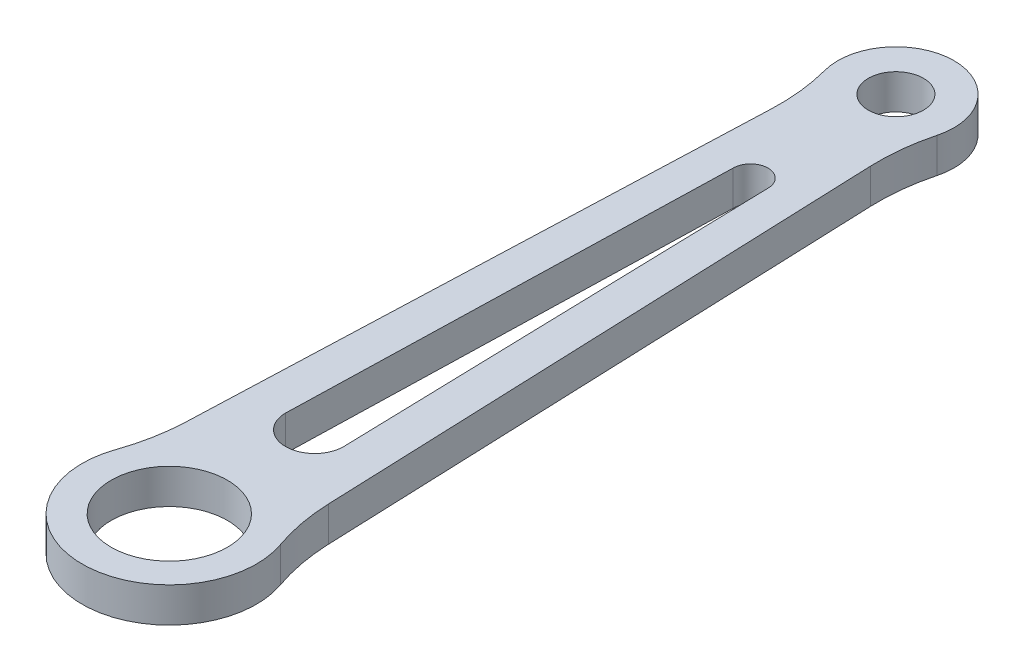
SolidWorks part; units mm, degrees
material "Thornel Mat VMA"
ref_plane "前视基准面" through (0, 0, 0) normal (0, 0, 1) x (1, 0, 0)
ref_plane "上视基准面" through (0, 0, 0) normal (0, 1, 0) x (1, 0, 0)
ref_plane "右视基准面" through (0, 0, 0) normal (1, 0, 0) x (0, 0, -1)
sketch "草图1" plane through (0, 0, 0) normal (0, 1, 0) x (1, 0, 0)
  line L0 (0, 0) -> (0, 250) construction
  line L1 (-17.9929, -0.504) -> (-24.9902, 249.3)
  line L2 (17.9929, -0.504) -> (24.9902, 249.3)
  line L3 (-11.9953, -0.336) -> (-18.9926, 249.468) construction
  line L4 (11.9953, -0.336) -> (18.9926, 249.468) construction
  line L5 (-16.4444, 158.5) -> (15.7446, 133.5146) construction
  line L6 (15.7446, 133.5146) -> (18.4752, 231) construction
  line L7 (18.4752, 231) -> (-18.0888, 217.2024) construction
  line L8 (-18.0888, 217.2024) -> (-16.4444, 158.5) construction
  line L9 (15.7446, 133.5146) -> (-18.0888, 217.2024) construction
  line L10 (18.5259, 134.639) -> (-15.3075, 218.3268) construction
  line L11 (12.9633, 132.3901) -> (-20.8701, 216.0779) construction
  line L12 (-16.4444, 158.5) -> (-17.7049, 203.5)
  line L13 (-17.7049, 203.5) -> (11.0289, 137.1749)
  line L14 (11.0289, 137.1749) -> (-16.4444, 158.5)
  line L15 (15.9543, 141) -> (18.4752, 231)
  line L16 (-15.3075, 218.3268) -> (-13.7162, 214.3907) construction
  line L17 (18.4752, 231) -> (-12, 219.5)
  line L18 (-12, 219.5) -> (15.9543, 141)
  circle A0 centre (0, 250) radius 25 construction
  circle A1 centre (0, 0) radius 18 construction
  circle A2 centre (0, 0) radius 5.05
  circle A3 centre (0, 250) radius 9.5
  arc A4 (-17.9929, -0.504) -> (17.9929, -0.504) centre (0, 0) ccw
  arc A5 (-24.9902, 249.3) -> (24.9902, 249.3) centre (0, 250) cw
  arc A6 (-18.9926, 249.468) -> (18.9926, 249.468) centre (0, 250) cw construction
  arc A7 (-11.9953, -0.336) -> (11.9953, -0.336) centre (0, 0) ccw construction
  dimension "D2" = 50
  dimension "D3" = 36
  dimension "D4" = 10.1
  dimension "D5" = 19
  dimension "D1" = 250
  dimension "D9" = 19
  dimension "D10" = 30.5
  dimension "D11" = 16
  dimension "D12" = 45
  dimension "D13" = 90
  dimension "D14" = 12
  dimension "D6" = 6
  dimension "D7" = 3
  dimension "D8" = 3
extrude "凸台-拉伸1" add sketch "草图1" along normal blind 12
fillet "圆角1" radius 3 6 edges at (18.4752, 6, -231) (-12, 6, -219.5) (-17.7049, 6, -203.5) (-16.4444, 6, -158.5) (15.9543, 6, -141) (11.0289, 6, -137.1749)
sketch "草图2" plane through (0, 12, 0) normal (0, 1, 0) x (1, 0, 0)
  line L0 (0, 250) -> (-15, 250) construction
  circle A0 centre (-15, 250) radius 2
  dimension "D2" = 4
  dimension "D1" = 15
extrude "切除-拉伸1" [suppressed] cut sketch "草图2" against normal through all
pattern_circular "阵列(圆周)1" [suppressed] count 3 over 360
sketch "草图3" plane through (0, 12, 0) normal (0, 1, 0) x (1, 0, 0)
  line L0 (0, 250) -> (14.25, 250) construction
  circle A0 centre (14.25, 250) radius 2
  dimension "D2" = 4
  dimension "D1" = 14.25
extrude "切除-拉伸2" [suppressed] cut sketch "草图3" against normal through all
pattern_circular "阵列(圆周)2" [suppressed] count 3 over 360
sketch "草图4" plane through (0, 12, 0) normal (0, 1, 0) x (1, 0, 0)
  line L2 (8.9965, -0.252) -> (15.9937, 249.552)
  line L3 (8.9965, -0.252) -> (15.9937, 249.552) construction
  line L4 (-13.0503, 144.4724) -> (12.4949, 124.6439)
  line L5 (-15.9937, 249.552) -> (-8.9965, -0.252)
  line L6 (-15.9937, 249.552) -> (-8.9965, -0.252) construction
  line L7 (-15.3248, 157.6309) -> (1.7846, 144.3504) construction
  line L8 (12.4949, 124.6439) -> (9.7421, 26.3657)
  line L9 (9.7421, 26.3657) -> (-10.1751, 41.8256)
  line L10 (-10.1751, 41.8256) -> (-13.0503, 144.4724)
  dimension "D3" = 9
  dimension "D1" = 9
  dimension "D2" = 9
extrude "切除-拉伸3" [suppressed] cut sketch "草图4" against normal through all
fillet "圆角2" [suppressed] radius 3
sketch "草图5" plane through (0, 12, 0) normal (0, 1, 0) x (1, 0, 0)
  circle A0 centre (0, 0) radius 27.5
  circle A1 centre (0, 0) radius 5.05
  dimension "D1" = 55
extrude "凸台-拉伸2" [suppressed] add sketch "草图5" against normal up to surface (10 mm away)
fillet "圆角3" [suppressed] radius 6
sketch "草图6" [suppressed] plane through (0, 15, 0) normal (0, 1, 0) x (1, 0, 0)
  line L0 (12.4949, 124.6439) -> (-10.1751, 41.8256) construction
  line L1 (-13.0503, 144.4724) -> (-10.1751, 41.8256) construction
  line L2 (9.6014, 125.4359) -> (-13.0687, 42.6176)
  line L3 (15.3885, 123.8518) -> (-7.2816, 41.0335)
  line L4 (-7.2816, 41.0335) -> (-7.6098, 39.8344)
  line L5 (-7.6098, 39.8344) -> (-13.0687, 42.6176)
  line L6 (9.6014, 125.4359) -> (9.9296, 126.6351)
  line L7 (9.9296, 126.6351) -> (15.3885, 123.8518)
  line L8 (-10.1751, 41.8256) -> (9.7421, 26.3657) construction
  line L9 (12.4949, 124.6439) -> (-13.0503, 144.4724) construction
  dimension "D1" = 3
  dimension "D2" = 3
extrude "凸台-拉伸3" [suppressed] add sketch "草图6" against normal up to surface (15 mm away)
fillet "圆角4" [suppressed] radius 3
sketch "草图7" plane through (0, 12, 0) normal (0, 1, 0) x (1, 0, 0)
  line L1 (15, 15) -> (-15, 15) construction
  line L2 (15, 15) -> (15, -15) construction
  line L3 (15, -15) -> (-15, -15) construction
  line L4 (-15, 15) -> (-15, -15) construction
  circle A0 centre (0, 0) radius 5.05 construction
  circle A1 centre (15, 15) radius 2.05
  circle A2 centre (-15, 15) radius 2.05
  circle A3 centre (-15, -15) radius 2.05
  circle A5 centre (15, -15) radius 2.05
  dimension "D2" = 15
  dimension "D4" = 4.1
  dimension "D1" = 30
  dimension "D3" = 15
extrude "切除-拉伸4" cut sketch "草图7" against normal through all
sketch "草图14" plane through (0, 12, 0) normal (0, 1, 0) x (1, 0, 0)
  line L0 (-17.9588, 235.1866) -> (21.3672, 232.9178)
  line L1 (21.3672, 232.9178) -> (15.5387, 131.8896)
  line L2 (15.5387, 131.8896) -> (-22.4973, 156.52)
  line L3 (-22.4973, 156.52) -> (-17.9588, 235.1866)
extrude "凸台-拉伸6" add sketch "草图14" against normal up to surface (12 mm away) up to face at (-15, 0, -12.95)
sketch "草图8" plane through (0, 12, 0) normal (0, 1, 0) x (1, 0, 0)
  circle A0 centre (0, 0) radius 13
  dimension "D1" = 26
extrude "切除-拉伸5" cut sketch "草图8" against normal through all
sketch "草图9" plane through (0, 12, 0) normal (0, 1, 0) x (1, 0, 0)
  circle A0 centre (0, 0) radius 25
  circle A1 centre (0, 0) radius 13
  circle A2 centre (0, 0) radius 13 construction
  dimension "D1" = 50
extrude "凸台-拉伸4" add sketch "草图9" against normal up to surface (12 mm away) up to face at (0, 0, 13)
sketch "草图10" plane through (0, 12, 0) normal (0, 1, 0) x (1, 0, 0)
  line L0 (-40, 0) -> (-24.9902, 249.3)
  line L2 (-24.9902, 249.3) -> (-18.9931, 35.2031)
  line L3 (24.9902, 249.3) -> (18.9931, 35.2031)
  line L4 (40, 0) -> (24.9902, 249.3)
  arc A0 (18.9931, 35.2031) -> (-18.9931, 35.2031) centre (0, 0) ccw
  circle A4 centre (36.5567, 8.3581) radius 1.5
  circle A5 centre (33.3766, -17.0955) radius 1.5
  circle A6 centre (14.5791, -34.5499) radius 1.5
  circle A7 centre (-11.04, -35.8381) radius 1.5
  circle A8 centre (-31.4934, -20.3572) radius 1.5
  circle A9 centre (-37.2107, 4.6491) radius 1.5
  circle A11 centre (-1.8831, 37.4527) radius 1.5
  circle A12 centre (0, 0) radius 21.5
  arc A13 (-39.711, 4.7992) -> (39.711, 4.7992) centre (0, 0) ccw
extrude "凸台-拉伸5" add sketch "草图10" against normal up to surface (12 mm away)
sketch "草图12" plane through (0, 12, 0) normal (0, 1, 0) x (1, 0, 0)
  circle A0 centre (0, 0) radius 20.8885
  circle A1 centre (-1.8831, 37.4527) radius 1.5
sketch "草图13" plane through (0, 12, 0) normal (0, 1, 0) x (1, 0, 0)
  line L9 (0, 250) -> (0, 0) construction
  line L10 (39.2006, 250) -> (39.2005, 249.9361)
  line L12 (6, 200) -> (10, 50)
  line L14 (-6, 200) -> (-10, 50)
  line L44 (39.2005, 249.9361) -> (40, 0)
  line L45 (-39.2006, 250) -> (-40, 0)
  line L48 (-24.4773, 30.2431) -> (-17.0517, 224.2815)
  line L50 (24.4773, 30.2431) -> (17.0517, 224.2815)
  circle A8 centre (0, 0) radius 20
  arc A21 (39.2005, 249.9361) -> (-39.2006, 250) centre (0, 250) ccw
  arc A22 (-39.9992, 0.2558) -> (39.9992, 0.2559) centre (0, 0) ccw
  arc A25 (-28.3278, 9.876) -> (28.3278, 9.876) centre (0, 0) ccw
  arc A26 (-39.9992, 0.2558) -> (39.9992, 0.2559) centre (0, 0) ccw
  circle A27 centre (0, 250) radius 9.5
  arc A28 (19.3334, 244.8796) -> (-19.3334, 244.8796) centre (0, 250) ccw
  arc A29 (28.3278, 9.876) -> (24.4773, 30.2431) centre (94.4261, 32.9199) cw
  arc A30 (-28.3278, 9.876) -> (-24.4773, 30.2431) centre (-94.4261, 32.9199) ccw
  arc A31 (17.0517, 224.2815) -> (19.3334, 244.8796) centre (87.0005, 226.9583) cw
  arc A32 (-17.0517, 224.2815) -> (-19.3334, 244.8796) centre (-87.0005, 226.9583) ccw
  arc A33 (6, 200) -> (-6, 200) centre (0, 200) ccw
  arc A34 (-9.9858, 50.533) -> (9.9858, 50.533) centre (0, 50) ccw
  point P20 (34.8746, 28.4388)
  point P22 (14.0279, 72.2285)
  point P30 (-14.6515, 94.4897)
  dimension "D1" = 70
  dimension "D2" = 70
  dimension "D3" = 6
  dimension "D4" = 150
  dimension "D5" = 50
extrude "切除-拉伸6" cut sketch "草图13" against normal blind 25
